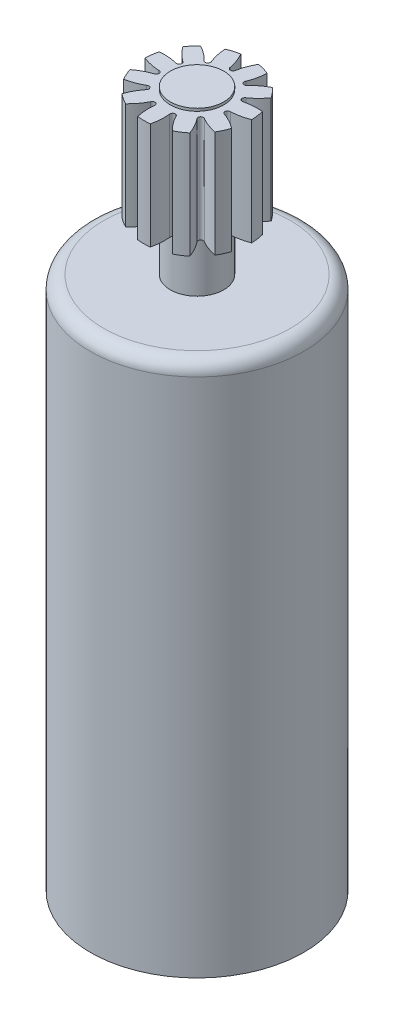
SolidWorks part; units mm, degrees
ref_plane "Front Plane" through (0, 0, 0) normal (0, 0, 1) x (1, 0, 0)
ref_plane "Top Plane" through (0, 0, 0) normal (0, 1, 0) x (1, 0, 0)
ref_plane "Right Plane" through (0, 0, 0) normal (1, 0, 0) x (0, 0, -1)
sketch "Sketch4" plane through (0, 0, 0) normal (1, 0, 0) x (0, 0, -1)
  line L0 (0, 0) -> (0, 26.1)
  line L1 (0, 26.1) -> (1, 26.1)
  line L2 (1, 26.1) -> (1, 26)
  line L3 (1, 26) -> (2, 26)
  line L4 (2, 26) -> (2, 22)
  line L5 (2, 22) -> (1, 22)
  line L6 (1, 22) -> (1, 20)
  line L7 (1, 20) -> (3.5, 20)
  line L8 (4, 19.5) -> (4, 0)
  line L9 (4, 0) -> (0, 0)
  arc A0 (4, 19.5) -> (3.5, 20) centre (3.5, 19.5) ccw
  point P15 (4, 20)
  dimension "D8" = 0.5
  dimension "D1" = 4
  dimension "D2" = 1
  dimension "D3" = 0.1
  dimension "D4" = 26.1
  dimension "D5" = 3
  dimension "D6" = 4
  dimension "D7" = 2
  dimension "D9" = 1
revolve "Revolve1" add sketch "Sketch4" angle 360 about L0
sketch "Sketch5" plane through (0, 26, 0) normal (0, 1, 0) x (1, 0, 0)
  line L0 (0, 0) -> (0, 2) construction
  circle A0 centre (0, 0) radius 2 construction
  arc A1 (0.3325, 1.9722) -> (0.1, 1.35) centre (2.0637, 0.9707) ccw
  arc A2 (-0.3325, 1.9722) -> (0.3325, 1.9722) centre (0, 0) cw
  arc A3 (0.1, 1.35) -> (-0.1, 1.35) centre (0, 1.35) cw
  arc A4 (-0.3325, 1.9722) -> (-0.1, 1.35) centre (-2.0637, 0.9707) cw
  dimension "D2" = 0.1
extrude "Cut-Extrude2" cut sketch "Sketch5" against normal blind 5
pattern_circular "CirPattern1" count 11 over 360 about axis through (0, 0, 0) along (0, 1, 0) of "Cut-Extrude2"
